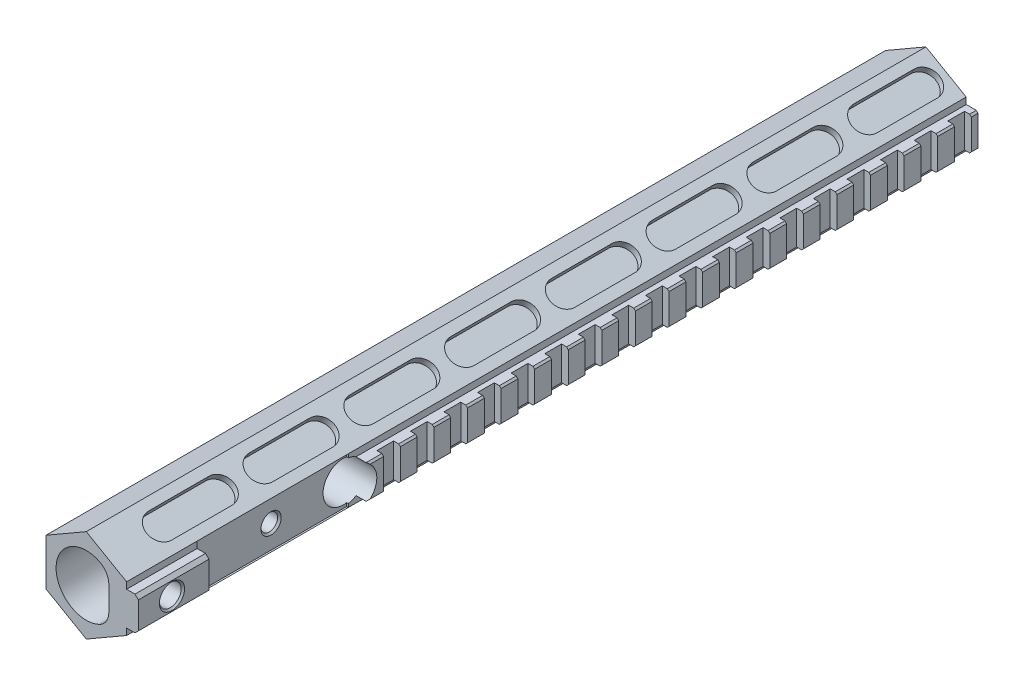
SolidWorks part; units mm, degrees
ref_plane "前视基准面" through (0, 0, 0) normal (0, 0, 1) x (1, 0, 0)
ref_plane "上视基准面" through (0, 0, 0) normal (0, 1, 0) x (1, 0, 0)
ref_plane "右视基准面" through (0, 0, 0) normal (1, 0, 0) x (0, 0, -1)
sketch "草图1" plane through (0, 0, 0) normal (0, 0, 1) x (1, 0, 0)
  line L1 (0, -13.8564) -> (12, -6.9282)
  line L2 (12, -6.9282) -> (12, 6.9282)
  line L3 (12, 6.9282) -> (0, 13.8564)
  line L4 (0, 13.8564) -> (-12, 6.9282)
  line L5 (-12, 6.9282) -> (-12, -6.9282)
  line L6 (-12, -6.9282) -> (0, -13.8564)
  circle A0 centre (0, 0) radius 13.8564 construction
  dimension "D1" = 24
extrude "凸台-拉伸1" add sketch "草图1" against normal blind 250
sketch "草图8" plane through (6, -10.3923, 0) normal (0.5, -0.866, 0) x (0.866, 0.5, 0)
  line L0 (-0.0282, -16) -> (-0.0282, -34) construction
  line L1 (-6.9282, -250) -> (-6.9282, 0) construction
  line L2 (3.9718, -16) -> (3.9718, -34)
  line L3 (-4.0282, -16) -> (-4.0282, -34)
  line L4 (-6.9282, 0) -> (6.9282, 0) construction
  line L5 (-0.0282, -46) -> (-0.0282, -64) construction
  line L6 (3.9718, -46) -> (3.9718, -64)
  line L7 (-4.0282, -46) -> (-4.0282, -64)
  line L8 (-0.0282, -76) -> (-0.0282, -94) construction
  line L9 (3.9718, -76) -> (3.9718, -94)
  line L10 (-4.0282, -76) -> (-4.0282, -94)
  line L11 (-0.0282, -106) -> (-0.0282, -124) construction
  line L12 (3.9718, -106) -> (3.9718, -124)
  line L13 (-4.0282, -106) -> (-4.0282, -124)
  line L14 (-0.0282, -136) -> (-0.0282, -154) construction
  line L15 (3.9718, -136) -> (3.9718, -154)
  line L16 (-4.0282, -136) -> (-4.0282, -154)
  line L17 (-0.0282, -166) -> (-0.0282, -184) construction
  line L18 (3.9718, -166) -> (3.9718, -184)
  line L19 (-4.0282, -166) -> (-4.0282, -184)
  line L20 (-0.0282, -196) -> (-0.0282, -214) construction
  line L21 (3.9718, -196) -> (3.9718, -214)
  line L22 (-4.0282, -196) -> (-4.0282, -214)
  line L23 (-0.0282, -226) -> (-0.0282, -244) construction
  line L24 (3.9718, -226) -> (3.9718, -244)
  line L25 (-4.0282, -226) -> (-4.0282, -244)
  arc A0 (3.9718, -16) -> (-4.0282, -16) centre (-0.0282, -16) ccw
  arc A1 (-4.0282, -34) -> (3.9718, -34) centre (-0.0282, -34) ccw
  arc A2 (3.9718, -46) -> (-4.0282, -46) centre (-0.0282, -46) ccw
  arc A3 (-4.0282, -64) -> (3.9718, -64) centre (-0.0282, -64) ccw
  arc A4 (3.9718, -76) -> (-4.0282, -76) centre (-0.0282, -76) ccw
  arc A5 (-4.0282, -94) -> (3.9718, -94) centre (-0.0282, -94) ccw
  arc A6 (3.9718, -106) -> (-4.0282, -106) centre (-0.0282, -106) ccw
  arc A7 (-4.0282, -124) -> (3.9718, -124) centre (-0.0282, -124) ccw
  arc A8 (3.9718, -136) -> (-4.0282, -136) centre (-0.0282, -136) ccw
  arc A9 (-4.0282, -154) -> (3.9718, -154) centre (-0.0282, -154) ccw
  arc A10 (3.9718, -166) -> (-4.0282, -166) centre (-0.0282, -166) ccw
  arc A11 (-4.0282, -184) -> (3.9718, -184) centre (-0.0282, -184) ccw
  arc A12 (3.9718, -196) -> (-4.0282, -196) centre (-0.0282, -196) ccw
  arc A13 (-4.0282, -214) -> (3.9718, -214) centre (-0.0282, -214) ccw
  arc A14 (3.9718, -226) -> (-4.0282, -226) centre (-0.0282, -226) ccw
  arc A15 (-4.0282, -244) -> (3.9718, -244) centre (-0.0282, -244) ccw
  point P4 (-0.0282, -25)
  point P15 (-0.0282, -55)
  point P22 (-0.0282, -85)
  point P29 (-0.0282, -115)
  point P36 (-0.0282, -145)
  point P43 (-0.0282, -175)
  point P50 (-0.0282, -205)
  point P57 (-0.0282, -235)
  dimension "D1" = 2.9
  dimension "D2" = 8
  dimension "D3" = 18
  dimension "D4" = 16
  dimension "D6" = 12
  dimension "D5" = 8
extrude "切除-拉伸1" cut sketch "草图8" against normal blind 2
mirror "镜向2" about plane through (0, 0, 0) normal (0, 1, 0) of "切除-拉伸1"
hole_wizard "M8 螺纹孔1" positions "草图16" profile "草图17" tap size "M8" standard "GB"
sketch "草图16" plane through (0, 0, -250) normal (0, 0, -1) x (-1, 0, 0)
  point P0 (0, 0)
sketch "草图17" plane through (0, 0, -250) normal (1, 0, 0) x (0, 1, 0)
  line L0 (0, 0) -> (0, 27.0429)
  line L1 (0, 27.0429) -> (3.4, 25)
  line L2 (3.4, 25) -> (3.4, 0)
  line L5 (3.4, 0) -> (0, 0)
  line L10 (0, 27.0429) -> (-3.4, 25) construction
  line L11 (0, -6.35) -> (0, 107.95) construction
  dimension "螺纹孔钻头直径" = 6.8
  dimension "螺纹孔钻头深度" = 25
  dimension "导头角度" = 118
cosmetic thread "孔螺蚊线1" parameters "D1"=20, "D2"=8
hole_wizard "M6 螺纹孔2" positions "草图21" profile "草图22" tap size "M6" standard "GB"
sketch "草图21" plane through (-12, 0, 0) normal (-1, 0, 0) x (0, 0, 1)
  line L0 (-250, 6.9282) -> (-250, -6.9282) construction
  point P0 (-170, 0)
  dimension "D1" = 80
sketch "草图22" plane through (-12, 0, -170) normal (0, 1, 0) x (0, 0, 1)
  line L0 (0, 0) -> (0, 16.5022)
  line L1 (0, 16.5022) -> (2.5, 15)
  line L2 (2.5, 15) -> (2.5, 0)
  line L5 (2.5, 0) -> (0, 0)
  line L10 (0, 16.5022) -> (-2.5, 15) construction
  line L11 (0, -6.35) -> (0, 107.95) construction
  dimension "螺纹孔钻头直径" = 5
  dimension "螺纹孔钻头深度" = 15
  dimension "导头角度" = 118
cosmetic thread "孔螺蚊线4" parameters "D1"=12, "D2"=6
sketch "草图32" plane through (0, 0, 0) normal (0, 0, 1) x (1, 0, 0)
  line L1 (6.7, 3.6208) -> (6.7, -3.6208)
  arc A0 (3.825, 8.1467) -> (3.825, -8.1467) centre (0, 0) ccw
  arc A4 (3.825, -8.1467) -> (6.7, -3.6208) centre (1.7, -3.6208) ccw
  arc A5 (6.7, 3.6208) -> (3.825, 8.1467) centre (1.7, 3.6208) ccw
  dimension "D1" = 18
  dimension "D2" = 10
  dimension "D3" = 15.7
extrude "切除-拉伸2" cut sketch "草图32" against normal blind 21
sketch "草图39" plane through (0, 0, 0) normal (0, 0, 1) x (1, 0, 0)
  line L0 (-14.7494, 0) -> (15.6712, 0) construction
  line L1 (12, 5) -> (12, -5)
  line L2 (12, -6.9282) -> (12, 6.9282) construction
  line L3 (12, 5) -> (15.5, 5)
  line L4 (15.5, 5) -> (15.5, -5)
  line L5 (15.5, -5) -> (12, -5)
  line L6 (-12, 6.9282) -> (-12, -6.9282) construction
  point P7 (12, 0)
  dimension "D1" = 10
  dimension "D2" = 27.5
extrude "凸台-拉伸6" add sketch "草图39" against normal blind 250
sketch "草图40" plane through (15.5, 0, 0) normal (1, 0, 0) x (0, 0, -1)
  line L0 (21, 6.9282) -> (21, -6.9282)
  line L3 (21, -6.9282) -> (66, -6.9282)
  line L4 (21, 6.9282) -> (66, 6.9282)
  line L5 (66, 6.9282) -> (66, -6.9282)
  line L6 (0, -5) -> (0, 5) construction
  line L7 (250, 6.9282) -> (0, 6.9282) construction
  line L8 (250, -6.9282) -> (0, -6.9282) construction
  dimension "D1" = 45
  dimension "D2" = 21
extrude "切除-拉伸3" cut sketch "草图40" against normal blind 4
sketch "草图41" plane through (15.5, 0, 0) normal (1, 0, 0) x (0, 0, -1)
  line L0 (248, 5) -> (248, -5)
  line L1 (250, 5) -> (66, 5) construction
  line L2 (250, -5) -> (66, -5) construction
  line L3 (248, -5) -> (243, -5)
  line L4 (243, -5) -> (243, 5)
  line L5 (250, 5) -> (66, 5) construction
  line L6 (228, 5) -> (223, 5)
  line L7 (238, 5) -> (238, -5)
  line L8 (250, -5) -> (66, -5) construction
  line L9 (250, -5) -> (250, 5) construction
  line L10 (243, 5) -> (248, 5)
  line L11 (238, -5) -> (233, -5)
  line L12 (233, -5) -> (233, 5)
  line L13 (238, 5) -> (233, 5)
  line L14 (223, -5) -> (223, 5)
  line L15 (228, -5) -> (223, -5)
  line L16 (228, 5) -> (228, -5)
  line L17 (218, 5) -> (213, 5)
  line L18 (213, -5) -> (213, 5)
  line L19 (218, -5) -> (213, -5)
  line L20 (218, 5) -> (218, -5)
  line L21 (208, 5) -> (203, 5)
  line L22 (203, -5) -> (203, 5)
  line L23 (208, -5) -> (203, -5)
  line L24 (208, 5) -> (208, -5)
  line L25 (198, 5) -> (193, 5)
  line L26 (193, -5) -> (193, 5)
  line L27 (198, -5) -> (193, -5)
  line L28 (198, 5) -> (198, -5)
  line L29 (188, 5) -> (183, 5)
  line L30 (183, -5) -> (183, 5)
  line L31 (188, -5) -> (183, -5)
  line L32 (188, 5) -> (188, -5)
  line L33 (178, 5) -> (173, 5)
  line L34 (173, -5) -> (173, 5)
  line L35 (178, -5) -> (173, -5)
  line L36 (178, 5) -> (178, -5)
  line L37 (168, 5) -> (163, 5)
  line L38 (163, -5) -> (163, 5)
  line L39 (168, -5) -> (163, -5)
  line L40 (168, 5) -> (168, -5)
  line L41 (158, 5) -> (153, 5)
  line L42 (153, -5) -> (153, 5)
  line L43 (158, -5) -> (153, -5)
  line L44 (158, 5) -> (158, -5)
  line L45 (148, 5) -> (143, 5)
  line L46 (143, -5) -> (143, 5)
  line L47 (148, -5) -> (143, -5)
  line L48 (148, 5) -> (148, -5)
  line L49 (138, 5) -> (133, 5)
  line L50 (133, -5) -> (133, 5)
  line L51 (138, -5) -> (133, -5)
  line L52 (138, 5) -> (138, -5)
  line L53 (128, 5) -> (123, 5)
  line L54 (123, -5) -> (123, 5)
  line L55 (128, -5) -> (123, -5)
  line L56 (128, 5) -> (128, -5)
  line L57 (118, 5) -> (113, 5)
  line L58 (113, -5) -> (113, 5)
  line L59 (118, -5) -> (113, -5)
  line L60 (118, 5) -> (118, -5)
  line L61 (108, 5) -> (103, 5)
  line L62 (103, -5) -> (103, 5)
  line L63 (108, -5) -> (103, -5)
  line L64 (108, 5) -> (108, -5)
  line L65 (98, 5) -> (93, 5)
  line L66 (93, -5) -> (93, 5)
  line L67 (98, -5) -> (93, -5)
  line L68 (98, 5) -> (98, -5)
  line L69 (88, 5) -> (83, 5)
  line L70 (83, -5) -> (83, 5)
  line L71 (88, -5) -> (83, -5)
  line L72 (88, 5) -> (88, -5)
  line L73 (78, 5) -> (73, 5)
  line L74 (73, -5) -> (73, 5)
  line L75 (78, -5) -> (73, -5)
  line L76 (78, 5) -> (78, -5)
  dimension "D1" = 2
  dimension "D2" = 5
  dimension "D3" = 5
  dimension "D4" = 17
extrude "切除-拉伸4" cut sketch "草图41" against normal blind 2
hole_wizard "孔1" positions "草图43" profile "草图44" legacy
sketch "草图43" plane through (15.5, 0, 0) normal (1, 0, 0) x (0, 0, -1)
  line L0 (0, -5) -> (0, 5) construction
  point P0 (10, 0)
  dimension "D1" = 10
sketch "草图44" plane through (15.5, 0, -10) normal (0, 1, 0) x (0, 0, -1)
  line L0 (0, 0) -> (0, 8.8)
  line L1 (0, 8.8) -> (3.25, 8.8)
  line L2 (3.25, 8.8) -> (3.25, 0)
  line L3 (3.25, 0) -> (0, 0)
  line L4 (0, 110) -> (0, -10) construction
  dimension "直径" = 6.5
  dimension "深度" = 8.8
hole_wizard "M6 螺纹孔3" positions "草图45" profile "草图47" tap size "M6" standard "GB"
sketch "草图45" plane through (11.5, 0, 0) normal (1, 0, 0) x (0, 0, -1)
  line L0 (66, -5) -> (66, 5) construction
  point P0 (43.5, 0)
  dimension "D1" = 22.5
sketch "草图47" plane through (11.5, 0, -43.5) normal (0, 1, 0) x (0, 0, -1)
  line L0 (0, 0) -> (0, 16.5022)
  line L1 (0, 16.5022) -> (2.5, 15)
  line L2 (2.5, 15) -> (2.5, 0.525)
  line L3 (2.5, 0.525) -> (3.025, 0)
  line L5 (3.025, 0) -> (0, 0)
  line L6 (-2.5, 0.525) -> (-3.025, 0) construction
  line L10 (0, 16.5022) -> (-2.5, 15) construction
  line L11 (0, -6.35) -> (0, 107.95) construction
  dimension "螺纹孔钻头直径" = 5
  dimension "螺纹孔钻头深度" = 15
  dimension "近端锥形沉头孔直径" = 6.05
  dimension "近端锥形沉头孔角度" = 90
  dimension "导头角度" = 118
cosmetic thread "孔螺蚊线5" parameters "D1"=12, "D2"=6
hole_wizard "孔2" positions "草图48" profile "草图50" legacy
sketch "草图48" plane through (15.5, 0, 0) normal (1, 0, 0) x (0, 0, -1)
  line L0 (250, -5) -> (250, 5) construction
  point P0 (65, 0)
  dimension "D1" = 185
sketch "草图50" plane through (15.5, 0, -65) normal (0, 1, 0) x (0, 0, -1)
  line L0 (0, 0) -> (0, 27.5)
  line L1 (0, 27.5) -> (3.25, 27.5)
  line L2 (3.25, 27.5) -> (3.25, 16)
  line L3 (3.25, 16) -> (6, 16)
  line L4 (6, 16) -> (6, 0)
  line L5 (6, 0) -> (0, 0)
  line L6 (0, 110) -> (0, -10) construction
  dimension "直径" = 6.5
  dimension "深度" = 27.5
  dimension "柱坑直径" = 12
  dimension "柱坑深度" = 16
chamfer "倒角5" distance 1 angle 45 2 edges at (15.5, 5, -10.5) (15.5, -5, -10.5)
chamfer "倒角6" distance 0.5 angle 45 1 edges at (15.5, 0, -13.25)
chamfer "倒角7" distance 0.5 angle 45 38 edges at (15.5, 5, -249) (15.5, -5, -249) (15.5, 5, -240.5) (15.5, -5, -240.5) (15.5, -5, -230.5) (15.5, -5, -220.5) (15.5, -5, -210.5) (15.5, 5, -230.5) (15.5, 5, -220.5) (15.5, 5, -210.5) (15.5, 5, -200.5) (15.5, -5, -200.5) (15.5, -5, -190.5) (15.5, -5, -180.5) (15.5, 5, -190.5) (15.5, 5, -180.5) (15.5, 5, -170.5) (15.5, 5, -160.5) (15.5, -5, -160.5) (15.5, -5, -170.5) (15.5, -5, -150.5) (15.5, 5, -150.5) (15.5, 5, -140.5) (15.5, -5, -140.5) (15.5, -5, -130.5) (15.5, 5, -130.5) (15.5, 5, -120.5) (15.5, -5, -120.5) (15.5, -5, -110.5) (15.5, 5, -110.5) (15.5, -5, -100.5) (15.5, 5, -100.5) (15.5, 5, -90.5) (15.5, -5, -90.5) (15.5, -5, -80.5) (15.5, 5, -80.5) (15.5, 5, -70.6583) (15.5, -5, -70.6583)
